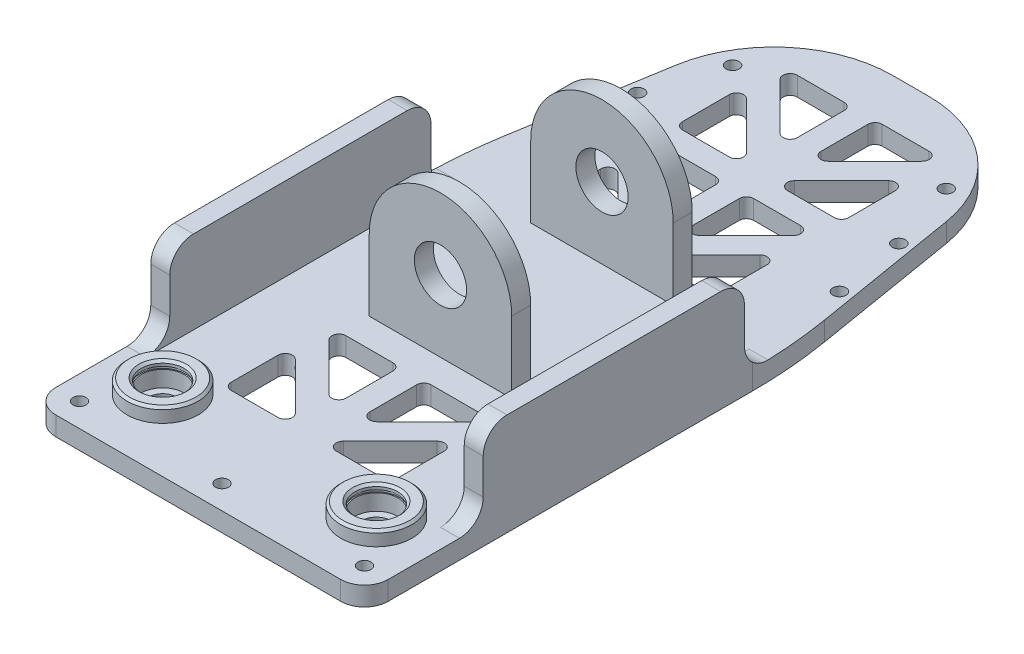
SolidWorks part; units mm, degrees
material "6061 合金"
ref_plane "前视基准面" through (0, 0, 0) normal (0, 0, 1) x (1, 0, 0)
ref_plane "上视基准面" through (0, 0, 0) normal (0, 1, 0) x (1, 0, 0)
ref_plane "右视基准面" through (0, 0, 0) normal (1, 0, 0) x (0, 0, -1)
other "Configuration Table"
sketch "草图1" plane through (0, 0, 0) normal (0, 1, 0) x (1, 0, 0)
  line L0 (0, 0) -> (0, 255.8207) construction
  line L1 (-70, 0) -> (70, 0)
  line L2 (70, 0) -> (70, 180)
  line L3 (70, 180) -> (50, 300)
  line L4 (50, 300) -> (-50, 300)
  line L5 (-70, 180) -> (-50, 300)
  line L6 (-70, 0) -> (-70, 180)
  point P8 (0, 300)
  dimension "D1" = 300
  dimension "D2" = 70
  dimension "D3" = 120
  dimension "D4" = 50
extrude "凸台-拉伸1" add sketch "草图1" along normal blind 8
sketch "草图2" plane through (70, 0, 0) normal (1, 0, 0) x (0, 0, -1)
  line L0 (40, 100) -> (40, -10.3339) construction
  line L1 (0, 8) -> (0, 0) construction
  line L2 (0, 8) -> (0, 58)
  line L3 (80, 8) -> (80, 58)
  arc A0 (80, 58) -> (0, 58) centre (40, 58) ccw
  circle A1 centre (40, 58) radius 10
  line M6 (180, 8) -> (0, 8)
  dimension "D3" = 20
  dimension "D1" = 40
  dimension "D2" = 50
extrude "凸台-拉伸2" [suppressed] add sketch "草图2" against normal up to surface (200 mm away) contours A0 L0 A1 L3 M6 | L0 A0 L2 A1 M6
sketch "草图3" [suppressed] plane through (0, 10, 0) normal (0, 1, 0) x (1, 0, 0)
  line L0 (0, 0) -> (0, 135.8056) construction
  line L1 (-100, 0) -> (100, 0) construction
  line L2 (-70, 0) -> (70, 0)
  line L3 (-70, 0) -> (-70, 100)
  line L4 (-70, 100) -> (70, 100)
  line L5 (70, 0) -> (70, 100)
  line L6 (100, 0) -> (100, 80) construction
  line L7 (-100, 80) -> (-100, 0) construction
  dimension "D1" = 30
  dimension "D2" = 30
  dimension "D3" = 100
extrude "切除-拉伸1" [suppressed] cut sketch "草图3" along normal blind 171
sketch "草图4" plane through (0, 0, 0) normal (0, 0, 1) x (1, 0, 0)
  line L0 (0, 0) -> (0, 92.3322) construction
  line L1 (30, 38) -> (30, 8)
  line L2 (-30, 38) -> (-30, 8)
  line L3 (-70, 8) -> (70, 8) construction
  arc A0 (-30, 38) -> (30, 38) centre (0, 38) cw
  circle A1 centre (0, 38) radius 11
  line M10 (70, 8) -> (-70, 8)
  dimension "D2" = 30
  dimension "D3" = 22
  dimension "D1" = 30
extrude "凸台-拉伸3" add sketch "草图4" against normal blind 80 from offset 100 contours L0 L1 A0 A1 M10 | L0 A1 A0 L2 M10 offset against normal yes
sketch "草图5" plane through (0, 8, 0) normal (0, 1, 0) x (1, 0, 0)
  line L0 (-47.074, 140) -> (51.1394, 140) construction
  line L1 (30, 180) -> (-30, 180) construction
  line L2 (30, 100) -> (-30, 100) construction
  line L3 (-30, 100) -> (30, 100) construction
  line L4 (-40, 170) -> (40, 170)
  line L5 (-40, 170) -> (-40, 110)
  line L6 (-40, 110) -> (40, 110)
  line L7 (40, 170) -> (40, 110)
  line L8 (30, 180) -> (30, 100) construction
  line L9 (-30, 180) -> (-30, 100) construction
  dimension "D1" = 10
  dimension "D2" = 10
  dimension "D3" = 10
  dimension "D4" = 10
extrude "切除-拉伸2" cut sketch "草图5" along normal blind 110 contours L7 L6 L5 L4
fillet "圆角1" radius 50 2 edges at (-50, 4, -300) (50, 4, -300)
fillet "圆角2" radius 200 2 edges at (-70, 4, -180) (70, 4, -180)
sketch "草图6" [suppressed] plane through (100, 0, 0) normal (1, 0, 0) x (0, 0, -1)
  line L0 (40, 60) -> (40, -52.2503) construction
  circle A0 centre (40, 60) radius 10 construction
  circle A1 centre (40, 60) radius 10 construction
  arc A2 (73.0468, 82.5368) -> (6.9532, 82.5368) centre (40, -25) ccw
  arc A3 (80, 60) -> (0, 60) centre (40, 60) ccw construction
  arc A4 (73.0468, 82.5368) -> (6.9532, 82.5368) centre (40, 60) ccw
  dimension "D2" = 225
  dimension "D1" = 25
extrude "切除-拉伸3" [suppressed] cut sketch "草图6" against normal through all both and the other way through all contours A2 A4
sketch "草图7" plane through (0, 8, 0) normal (0, 1, 0) x (1, 0, 0)
  line L0 (0, 0) -> (0, 141.3983) construction
  line L1 (-70, 0) -> (70, 0) construction
  line L2 (-136.8569, 140) -> (150.7223, 140) construction
  line L3 (-30, 170) -> (30, 170) construction
  line L4 (-30, 110) -> (30, 110) construction
  circle A0 centre (45, 30) radius 9
  dimension "D1" = 18
  dimension "D2" = 45
  dimension "D3" = 30
extrude "切除-拉伸6" cut sketch "草图7" against normal offset from surface (4 mm away) 4 contours A0 up to face at (0, 0, -185.4184)
sketch "草图10" plane through (0, 4, 0) normal (0, 1, 0) x (1, 0, 0)
  circle A0 centre (45, 30) radius 6
  dimension "D1" = 12
extrude "切除-拉伸7" cut sketch "草图10" against normal blind 28 contours A0
sketch "草图11" plane through (0, 8, 0) normal (0, 1, 0) x (1, 0, 0)
  circle A0 centre (45, 30) radius 12.5
  circle A1 centre (45, 30) radius 16.5
  dimension "D1" = 25
  dimension "D2" = 33
extrude "切除-拉伸8" [suppressed] cut sketch "草图11" against normal blind 5
sketch "草图12" plane through (0, 8, 0) normal (0, 1, 0) x (1, 0, 0)
  circle A0 centre (45, 30) radius 15
  dimension "D1" = 30
extrude "凸台-拉伸5" add sketch "草图12" along normal blind 6 contours A0
sketch "草图13" plane through (0, 14, 0) normal (0, 1, 0) x (1, 0, 0)
  circle A0 centre (45, 30) radius 9
  dimension "D1" = 18
extrude "切除-拉伸9" cut sketch "草图13" against normal blind 6
sketch "草图14" plane through (0, 14, 0) normal (0, 1, 0) x (1, 0, 0)
  circle A0 centre (45, 30) radius 9.5
  circle A2 centre (45, 30) radius 9 construction
  circle A3 centre (45, 30) radius 9
  dimension "D1" = 19
extrude "卡簧槽" cut sketch "草图14" against normal blind 1.1 from offset 2.15 contours A0 offset against normal yes
chamfer "倒角1" distance 1 angle 45 2 edges at (45, 14, -15) (45, 14, -21)
ref_plane "基准面1" through (0, 0, 0) normal (-1, 0, 0) x (0, 0, 1)
mirror "镜向1" about plane through (0, 0, 0) normal (-1, 0, 0) of "切除-拉伸6", "切除-拉伸7", "凸台-拉伸5", "切除-拉伸9", "卡簧槽", "倒角1"
sketch "草图16" plane through (0, 0, -100) normal (0, 0, 1) x (1, 0, 0)
  circle A0 centre (0, 38) radius 13
  dimension "D1" = 26
extrude "切除-拉伸10" [suppressed] cut sketch "草图16" against normal blind 0.75
sketch "草图17" plane through (0, 0, -180) normal (0, 0, -1) x (-1, 0, 0)
  circle A0 centre (0, 38) radius 13
  dimension "D1" = 26
extrude "切除-拉伸11" [suppressed] cut sketch "草图17" against normal blind 0.75 contours A0
sketch "草图18" plane through (-70, 0, 0) normal (-1, 0, 0) x (0, 0, 1)
  line L0 (-30, 92.2697) -> (-30, -20.0308) construction
  line L1 (-40, 8) -> (-40, 28)
  line L2 (-163.4475, 8) -> (0, 8) construction
  line L3 (-20, 28) -> (-20, 8)
  line L4 (-40, 8) -> (-20, 8)
  arc A0 (-20, 28) -> (-40, 28) centre (-30, 28) ccw
  circle A1 centre (-30, 28) radius 2.5
  dimension "D2" = 5
  dimension "D4" = 10
  dimension "D1" = 30
  dimension "D3" = 20
extrude "凸台-拉伸6" [suppressed] add sketch "草图18" against normal up to surface (200 mm away) contours A1 L0 | L0 A1 | L3 L4 L1 A0
sketch "草图20" plane through (0, 8, 0) normal (0, 1, 0) x (1, 0, 0)
  line L0 (0, 0) -> (0, 309.5578) construction
  line L1 (-70, 0) -> (70, 0) construction
  line L2 (-60.0864, 49.2403) -> (-60.0864, 11.6041)
  line L3 (75.0864, 51.8093) -> (107.8414, 51.8093)
  line L4 (75.0864, 51.8093) -> (75.0864, 7.1083)
  line L5 (75.0864, 7.1083) -> (107.8414, 7.1083)
  line L6 (107.8414, 51.8093) -> (107.8414, 7.1083)
  line L7 (15, 49.2403) -> (60.0864, 49.2403)
  line L8 (15, 49.2403) -> (15, 11.6041)
  line L9 (15, 11.6041) -> (60.0864, 11.6041)
  line L10 (60.0864, 49.2403) -> (60.0864, 11.6041)
  line L11 (-15, 11.6041) -> (-60.0864, 11.6041)
  line L12 (-15, 49.2403) -> (-15, 11.6041)
  line L13 (-15, 49.2403) -> (-60.0864, 49.2403)
  line L14 (-107.8414, 51.8093) -> (-107.8414, 7.1083)
  line L15 (-75.0864, 7.1083) -> (-107.8414, 7.1083)
  line L16 (-75.0864, 51.8093) -> (-75.0864, 7.1083)
  line L17 (-75.0864, 51.8093) -> (-107.8414, 51.8093)
  dimension "D1" = 15
  dimension "D2" = 15
extrude "切除-拉伸12" [suppressed] cut sketch "草图20" along normal through all
chamfer "倒角2" [suppressed] distance 30 distance2 60
chamfer "倒角3" [suppressed] distance 60 distance2 30
fillet "圆角3" [suppressed] radius 10
ref_plane "脚底板中心面" through (0, 0, 0) normal (-1, 0, 0) x (0, 0, 1)
ref_plane "基准面3" through (0, 0, -30) normal (0, 0, 1) x (1, 0, 0)
sketch "草图22" plane through (0, 0, -30) normal (0, 0, 1) x (1, 0, 0)
  line L0 (45, 18.5577) -> (45, -23.1228) construction
  line L1 (-45, 24.8334) -> (-45, -23.1228) construction
  line L2 (45, 0) -> (45, 4) construction
  line L3 (-45, 0) -> (-45, 4) construction
ref_plane "基准面4" through (-45, 0, 0) normal (-1, 0, 0) x (0, 0, 1)
sketch "草图23" plane through (0, 8, 0) normal (0, 1, 0) x (1, 0, 0)
  line L0 (0, 0) -> (0, 305.986) construction
  line L1 (-112.464, 150) -> (123.7617, 150) construction
  line L4 (7.6436, 300) -> (-7.6436, 300) construction
  line L5 (-70, 0) -> (70, 0) construction
  line L6 (70, 0) -> (70, 163.4475) construction
  line L7 (62, 160) -> (70, 160)
  line L8 (62, 160) -> (62, 50)
  line L9 (62, 50) -> (70, 50)
  line L10 (70, 160) -> (70, 50)
  line L11 (-62, 50) -> (-70, 50)
  line L12 (-70, 160) -> (-70, 50)
  line L13 (-62, 160) -> (-70, 160)
  line L14 (-62, 160) -> (-62, 50)
  dimension "D1" = 8
  dimension "D2" = 50
  dimension "D3" = 110
extrude "凸台-拉伸7" add sketch "草图23" along normal blind 35
fillet "圆角5" radius 10 10 edges at (70, 4, 0) (-70, 4, 0) (-66, 43, -160) (-66, 8, -160) (-66, 43, -50) (-66, 8, -50) (66, 43, -160) (66, 8, -160) (66, 8, -50) (66, 43, -50)
other "移动面1" face at (11, 38, -180) face at (11, 38, -100) parameters "D1"=2
sketch "草图24" plane through (0, 8, 0) normal (0, 1, 0) x (1, 0, 0)
  line L0 (0, 310.351) -> (0, -16.2567) construction
  line L1 (5, 90) -> (35, 90)
  line L2 (35, 90) -> (5, 60)
  line L3 (5, 60) -> (5, 90)
  line L4 (35, 75.8579) -> (5, 45.8579)
  line L5 (5, 45.8579) -> (35, 45.8579)
  line L6 (35, 45.8579) -> (35, 75.8579)
  line L7 (-60, 0) -> (60, 0) construction
  line L8 (-5, 45.8579) -> (-35, 45.8579)
  line L9 (-35, 75.8579) -> (-5, 45.8579)
  line L10 (-35, 45.8579) -> (-35, 75.8579)
  line L11 (-35, 90) -> (-5, 60)
  line L12 (-5, 90) -> (-35, 90)
  line L13 (-5, 60) -> (-5, 90)
  line L14 (5, 280) -> (35, 280)
  line L15 (35, 280) -> (5, 250)
  line L16 (5, 250) -> (5, 280)
  line L17 (35, 265.8579) -> (5, 235.8579)
  line L18 (5, 235.8579) -> (35, 235.8579)
  line L19 (35, 235.8579) -> (35, 265.8579)
  line L26 (5, 225.8579) -> (35, 225.8579)
  line L27 (35, 225.8579) -> (5, 195.8579)
  line L28 (5, 195.8579) -> (5, 225.8579)
  line L29 (35, 211.7157) -> (5, 181.7157)
  line L30 (5, 181.7157) -> (35, 181.7157)
  line L31 (35, 181.7157) -> (35, 211.7157)
  line L38 (-35, 181.7157) -> (-35, 211.7157)
  line L39 (-5, 181.7157) -> (-35, 181.7157)
  line L40 (-35, 211.7157) -> (-5, 181.7157)
  line L41 (-5, 195.8579) -> (-5, 225.8579)
  line L42 (-35, 225.8579) -> (-5, 195.8579)
  line L43 (-5, 225.8579) -> (-35, 225.8579)
  line L44 (-35, 235.8579) -> (-35, 265.8579)
  line L45 (-5, 235.8579) -> (-35, 235.8579)
  line L46 (-35, 265.8579) -> (-5, 235.8579)
  line L47 (-5, 250) -> (-5, 280)
  line L48 (-35, 280) -> (-5, 250)
  line L49 (-5, 280) -> (-35, 280)
  line L50 (7.6436, 300) -> (-7.6436, 300) construction
  circle A0 centre (45, 270) radius 2.75
  circle A1 centre (55, 240) radius 2.75
  circle A2 centre (60, 210) radius 2.75
  circle A3 centre (60, 10) radius 2.75
  circle A4 centre (0, 10) radius 2.75
  circle A5 centre (-60, 10) radius 2.75
  circle A6 centre (-60, 210) radius 2.75
  circle A7 centre (-55, 240) radius 2.75
  circle A8 centre (-45, 270) radius 2.75
  point P31 (0, 0)
  dimension "D13" = 5.5
  dimension "D20" = 5.5
  dimension "D23" = 5.5
  dimension "D1" = 30
  dimension "D2" = 30
  dimension "D3" = 5
  dimension "D4" = 90
  dimension "D5" = 10
  dimension "D6" = 30
  dimension "D7" = 30
  dimension "D8" = 10
  dimension "D9" = 10
  dimension "D10" = 30
  dimension "D11" = 10
  dimension "D12" = 280
  dimension "D14" = 45
  dimension "D15" = 55
  dimension "D16" = 60
  dimension "D17" = 30
  dimension "D18" = 60
  dimension "D19" = 90
  dimension "D21" = 60
  dimension "D22" = 10
extrude "切除-拉伸13" cut sketch "草图24" against normal blind 40
fillet "圆角6" radius 3 36 edges at (35, 4, -45.8579) (5, 4, -45.8579) (35, 4, -75.8579) (35, 4, -90) (5, 4, -90) (5, 4, -60) (-35, 4, -90) (-5, 4, -90) (-5, 4, -60) (-5, 4, -45.8579) (-35, 4, -45.8579) (-35, 4, -75.8579) (-5, 4, -181.7157) (-35, 4, -181.7157) (-35, 4, -211.7157) (35, 4, -211.7157) (35, 4, -181.7157) (5, 4, -181.7157) (-35, 4, -225.8579) (-5, 4, -225.8579) (-5, 4, -195.8579) (5, 4, -195.8579) (5, 4, -225.8579) (35, 4, -225.8579) (35, 4, -265.8579) (35, 4, -235.8579) (5, 4, -235.8579) (-35, 4, -235.8579) (-5, 4, -235.8579) (-35, 4, -265.8579) (-35, 4, -280) (-5, 4, -280) (-5, 4, -250) (5, 4, -250) (5, 4, -280) (35, 4, -280)
